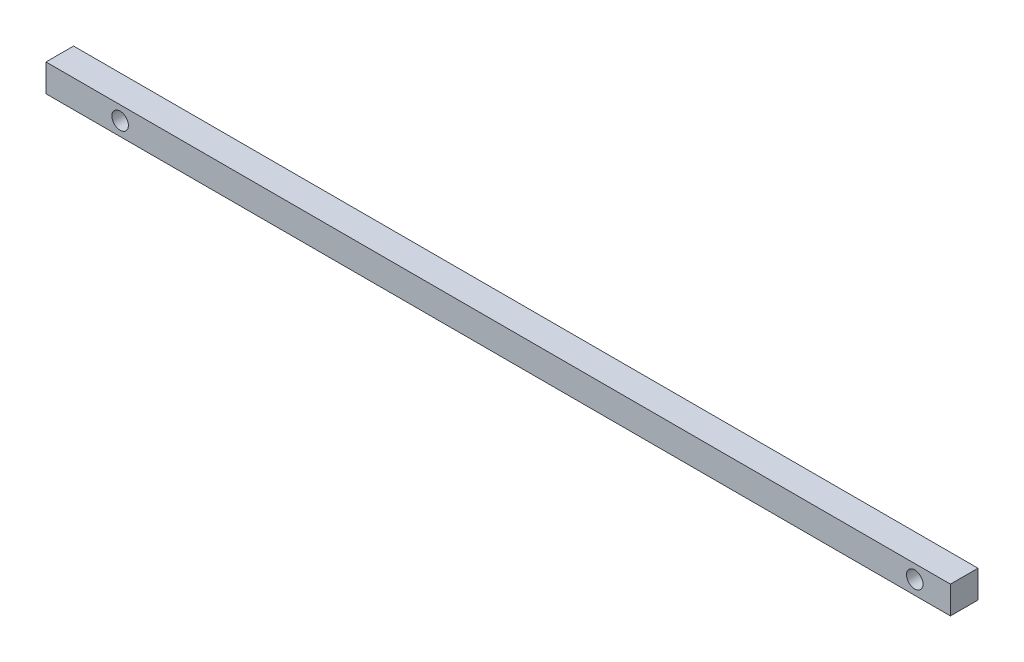
SolidWorks part; units mm, degrees
ref_plane "Front Plane" through (0, 0, 0) normal (0, 0, 1) x (1, 0, 0)
ref_plane "Top Plane" through (0, 0, 0) normal (0, 1, 0) x (1, 0, 0)
ref_plane "Right Plane" through (0, 0, 0) normal (1, 0, 0) x (0, 0, -1)
sketch "Sketch1" plane through (0, 0, 0) normal (0, 0, 1) x (1, 0, 0)
  line L0 (-562.0335, 0) -> (664.0431, 0) construction
  line L1 (0, 339.378) -> (0, -380.5742) construction
  line L3 (-410, 12.5) -> (410, 12.5)
  line L4 (-410, 12.5) -> (-410, -12.5)
  line L5 (-410, -12.5) -> (410, -12.5)
  line L6 (410, 12.5) -> (410, -12.5)
  line L7 (-410, 12.5) -> (410, -12.5) construction
  line L8 (-410, -12.5) -> (410, 12.5) construction
  circle A0 centre (-342.7871, 0) radius 7.5
  circle A1 centre (377.6429, 0) radius 7.5
  point P5 (0, 0)
  dimension "D2" = 15
  dimension "D3" = 15
  dimension "D1" = 820
  dimension "D4" = 720.43
  dimension "D5" = 25
extrude "Boss-Extrude1" add sketch "Sketch1" along normal blind 25
